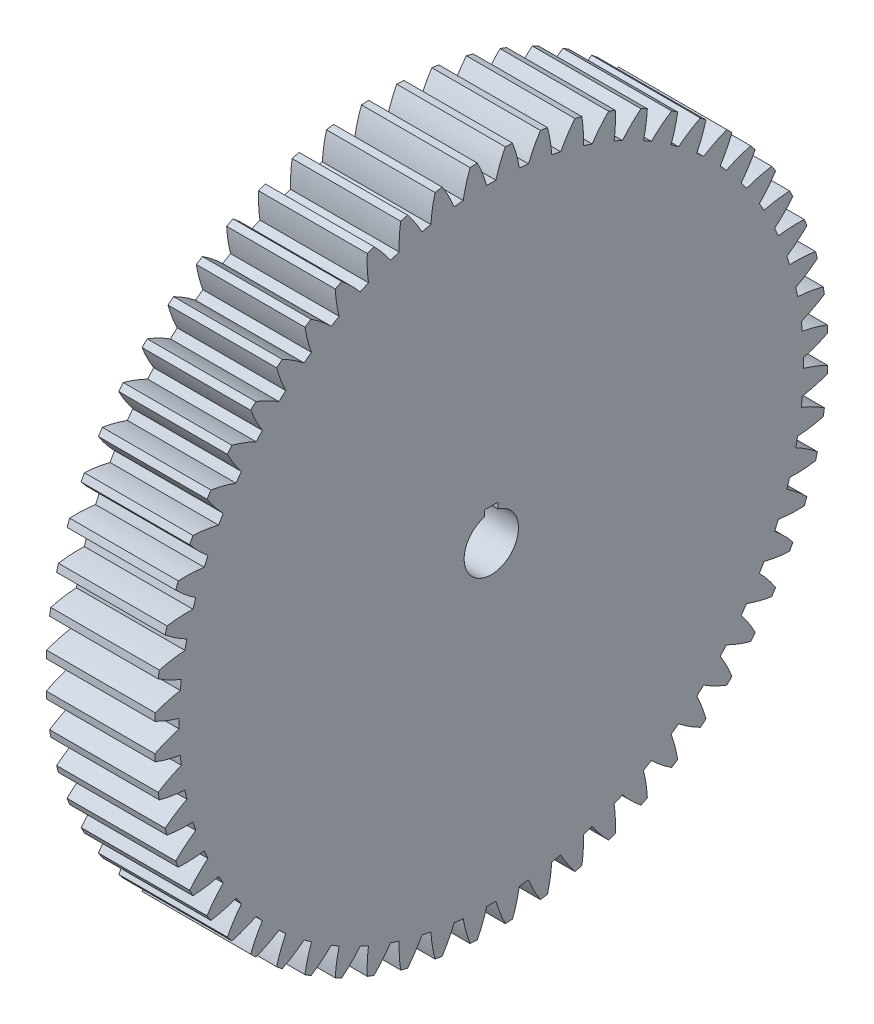
SolidWorks part; units mm, degrees
ref_plane "Plane1" through (0, 0, 0) normal (0, 0, 1) x (1, 0, 0)
ref_plane "Plane2" through (0, 0, 0) normal (0, 1, 0) x (1, 0, 0)
ref_plane "Plane3" through (0, 0, 0) normal (1, 0, 0) x (0, 0, -1)
sketch "HoldingSke" plane through (0, 0, 0) normal (0, 1, 0) x (1, 0, 0)
  line L0 (0, 0) -> (0.1, -0.1732)
  line L1 (-15, 0) -> (100, 0) construction
  line L2 (0, 0) -> (-2.1039, 2.3779)
  line L3 (0, 0) -> (-11.863, 4.5341)
  line L4 (0, 0) -> (4.318, 7.479)
  line L5 (0, 0) -> (-46.8476, -17.4728)
  line L6 (0, 0) -> (-41.4481, -27.9652)
  line L7 (-2.1039, 2.3779) -> (8.6586, 51.2059)
  line L8 (-76.2, 54.61) -> (-72.9, 54.61)
  line L9 (-71.009, 38.7566) -> (-53.1078, 45.2721)
  line L10 (-76.2, 71.12) -> (104.1128, 71.12)
  line L11 (0, 0) -> (-50, 0)
  line L12 (-76.2, 101.6) -> (-76.033, 101.6)
  line L13 (24.9733, 27.94) -> (52.9518, 28.4284)
  line L14 (24.9733, 27.94) -> (24.9743, 27.94)
  line L15 (24.9733, 27.94) -> (100.4006, 29.5858)
  line L16 (-63.627, -5) -> (-12.827, -5)
  circle A0 centre (0, 0) radius 12.5
  circle A1 centre (0, 0) radius 37.5
  circle A2 centre (0, 0) radius 37.5
  circle A3 centre (0, 0) radius 12.5
  dimension "MHD" = 75
  dimension "Hub_dia" = 75
  dimension "Bore" = 25
  dimension "MBD" = 25
  dimension "Num_teeth" = 60
  dimension "Pitch_radius" = 180.3128
  dimension "Pitch" = 0.2
  dimension "Width" = 50
  dimension "Overall_len" = 50
  dimension "Show_teeth" = 60
  dimension "Thickness" = 50
  dimension "OAL" = 50.0001
  dimension "T_dim" = 3.3
  dimension "Ap" = 20
  dimension "H" = 19.05
  dimension "Backlash" = 0.167
  dimension "Addendum_fac" = 1
  dimension "Dedendum_fac" = 1.25
  dimension "Clearance_fac" = 0.25
  dimension "Dedendum_add" = 0.001
  dimension "Module" = 5
sketch "BasProSke" plane through (0, 0, 0) normal (0, 1, 0) x (1, 0, 0)
  line L0 (-10, 0) -> (60, 0) construction
  line L1 (0, 0) -> (0, 155)
  line L2 (0, 0) -> (50, 0)
  line L3 (50, 0) -> (50, 155)
  line L4 (50, 155) -> (0, 155)
  dimension "Diameter" = 310
  dimension "Thickness" = 50
revolve "Base-Revolve" add sketch "BasProSke" angle 360 about L0
sketch "TooCutSke" plane through (0, 0, 0) normal (1, 0, 0) x (0, 0, -1)
  line L1 (0, 0) -> (0, 107) construction
  line L2 (0, 0) -> (-4.2188, 149.9407) construction
  line L3 (0, 0) -> (-15.6962, 299.5009) construction
  line L4 (-4.2188, 149.9407) -> (-7.8481, 149.7505) construction
  arc A0 (2.1133, 143.7335) -> (-2.1133, 143.7335) centre (0, 0) ccw
  arc A1 (6.4708, 154.8903) -> (-6.4708, 154.8903) centre (0, 0) ccw
  circle A2 centre (0, 0) radius 150 construction
  circle A3 centre (0, 0) radius 140.9539 construction
  arc A4 (-2.1133, 143.7335) -> (-6.4708, 154.8903) centre (-59.9014, 127.5924) ccw
  arc A5 (6.4708, 154.8903) -> (2.1133, 143.7335) centre (59.9014, 127.5924) ccw
  dimension "Root_dia" = 287.498
  dimension "Overcut_dia" = 310.0508
  dimension "Pitch_dia" = 300
  dimension "Base_dia" = 281.9078
  dimension "Flank_rad" = 60
  dimension "Half_ang" = 3
  dimension "Half_CT" = 3.6343
extrude "ToothCut" cut sketch "TooCutSke" along normal through all
fillet "Breaks" [suppressed] radius 0.1
fillet "RootFillets" [suppressed] radius 1.251
pattern_circular "TeethCuts" count 60 every 6 about axis through (-10, 0, 0) along (1, 0, 0) of "ToothCut", "RootFillets", "Breaks"
sketch "HubNeaOneSke" plane through (0, 0, 0) normal (-1, 0, 0) x (0, 0, 1)
  circle A0 centre (0, 0) radius 37.5
  dimension "Diameter" = 75
extrude "HubNearOne" [suppressed] add sketch "HubNeaOneSke" along normal blind 12.7001
sketch "HubNeaBotSke" plane through (0, 0, 0) normal (-1, 0, 0) x (0, 0, 1)
  circle A0 centre (0, 0) radius 37.5
  dimension "Diameter" = 75
extrude "HubNearBoth" [suppressed] add sketch "HubNeaBotSke" along normal blind 6.35
ref_plane "FarPln" through (50, 0, 0) normal (1, 0, 0) x (0, 0, -1)
sketch "HubFarSke" plane through (50, 0, 0) normal (1, 0, 0) x (0, 0, -1)
  circle A0 centre (0, 0) radius 37.5
  dimension "Diameter" = 75
extrude "HubFar" [suppressed] add sketch "HubFarSke" along normal blind 6.35
sketch "BorSke" plane through (0, 0, 0) normal (1, 0, 0) x (0, 0, -1)
  circle A0 centre (0, 0) radius 12.5
  dimension "Diameter" = 25
extrude "Bore" cut sketch "BorSke" along normal mid plane 100.0001
sketch "KeySke" plane through (0, 0, 0) normal (1, 0, 0) x (0, 0, -1)
  line L0 (-3.175, 0) -> (-3.175, 14.8812)
  line L1 (-3.175, 14.8812) -> (3.175, 14.8812)
  line L2 (3.175, 14.8812) -> (3.175, 0)
  line L3 (0, 0) -> (0, 34) construction
  line L4 (-3.175, 0) -> (3.175, 0)
  dimension "Offset" = 14.8812
  dimension "Width" = 6.35
extrude "Keyway" cut sketch "KeySke" along normal mid plane 100.0001
pattern_circular "Keyway2" [suppressed] count 2 every 90 about axis through (-10, 0, 0) along (1, 0, 0)
equation "' \"Module@HoldingSke\" = 6.35"
equation "' \"Num_teeth@HoldingSke\" = 12"
equation "' \"Ap@HoldingSke\" =  20"
equation "' \"Width@HoldingSke\" = 0.5 * 25.4"
equation "' \"Hub_dia@HoldingSke\"= 1 * 25.4"
equation "' \"Overall_len@HoldingSke\" = 1.0 * 25.4"
equation "' \"Bore@HoldingSke\" = 0.75 * 25.4"
equation "' \"T_dim@HoldingSke\" = 0.1 * 25.4"
equation "' \"Width@KeySke\" = 0.25 * 25.4"
equation "' \"Show_teeth@HoldingSke\" = 13"
equation "' \"Backlash@HoldingSke\" = 0.009 * 25.4"
equation "' \"Addendum_fac@HoldingSke\" = 1.0"
equation "' \"Dedendum_fac@HoldingSke\" = 1.25"
equation "' \"Dedendum_add@HoldingSke\" = 0.00005 * 25.4"
equation "' \"Clearance_fac@HoldingSke\" = 0.25"
equation "\"Pitch@HoldingSke\" = 1 / \"Module@HoldingSke\""
equation "\"Overcut_dia@TooCutSke\" = (\"Num_teeth@HoldingSke\" + 2 * \"Addendum_fac@HoldingSke\") / \"Pitch@HoldingSke\" + 0.002 * 25.4"
equation "\"Pitch_dia@TooCutSke\" = \"Num_teeth@HoldingSke\" / \"Pitch@HoldingSke\""
equation "\"Base_dia@TooCutSke\" = \"Num_teeth@HoldingSke\" / \"Pitch@HoldingSke\" * cos((\"Ap@HoldingSke\"  * 3.14159265 / 180))"
equation "\"Root_dia@TooCutSke\" = (\"Num_teeth@HoldingSke\" + 2) / \"Pitch@HoldingSke\" - 2 * (\"Addendum_fac@HoldingSke\" + \"Dedendum_fac@HoldingSke\") / \"Pitch@HoldingSke\" - \"Dedendum_add@HoldingSke\" * 2"
equation "\"Half_ang@TooCutSke\" = 180 / \"Num_teeth@HoldingSke\""
equation "\"Half_CT@TooCutSke\" = \"Num_teeth@HoldingSke\" / \"Pitch@HoldingSke\" * sin((3.14159265 / 2 / \"Num_teeth@HoldingSke\")) / 2 - 7 * \"Backlash@HoldingSke\" / 4"
equation "\"Flank_rad@TooCutSke\" = \"Num_teeth@HoldingSke\" / \"Pitch@HoldingSke\" / 5"
equation "\"Radius@RootFillets\" = \"Clearance_fac@HoldingSke\" / \"Pitch@HoldingSke\" + \"Dedendum_add@HoldingSke\""
equation "\"Break_rad@Breaks\" = 0.02 / \"Pitch@HoldingSke\""
equation "\"Thickness@HoldingSke\" = \"Width@HoldingSke\""
equation "\"OAL@HoldingSke\" = \"Thickness@HoldingSke\""
equation "\"MHD@HoldingSke\" = (\"Num_teeth@HoldingSke\" + 2) / \"Pitch@HoldingSke\" - 2 * (\"Addendum_fac@HoldingSke\" + \"Dedendum_fac@HoldingSke\")  / \"Pitch@HoldingSke\" - \"Dedendum_add@HoldingSke\" * 2"
equation "\"MBD@HoldingSke\" = (\"Num_teeth@HoldingSke\" + 2) / \"Pitch@HoldingSke\" - 2 * (\"Addendum_fac@HoldingSke\" + \"Dedendum_fac@HoldingSke\")  / \"Pitch@HoldingSke\" - \"Dedendum_add@HoldingSke\" * 2 - 0.002 * 25.4"
equation "\"MHD@HoldingSke\" = ((sgn( \"MHD@HoldingSke\" - \"Hub_dia@HoldingSke\" )-1)*( \"MHD@HoldingSke\" - \"Hub_dia@HoldingSke\" ))/-2+ \"Hub_dia@HoldingSke\""
equation "\"MBD@HoldingSke\" = ((sgn( \"MBD@HoldingSke\" - \"Bore@HoldingSke\" )-1)*( \"MBD@HoldingSke\" - \"Bore@HoldingSke\" ))/-2+ \"Bore@HoldingSke\""
equation "\"OAL@HoldingSke\" = ((sgn( \"OAL@HoldingSke\" - \"Overall_len@HoldingSke\" )+1)*( \"OAL@HoldingSke\" - \"Overall_len@HoldingSke\" ))/2 + \"Overall_len@HoldingSke\" + 0.000002 * 25.4"
equation "\"Num_teeth@TeethCuts\" = int( \"Show_teeth@HoldingSke\" ) + 1"
equation "\"Num_teeth@TeethCuts\" = ((sgn( \"Num_teeth@TeethCuts\" - \"Num_teeth@HoldingSke\" )-1)*( \"Num_teeth@TeethCuts\" - \"Num_teeth@HoldingSke\" ))/-2+ \"Num_teeth@HoldingSke\""
equation "\"Num_teeth@TeethCuts\" = ((sgn( \"Num_teeth@TeethCuts\" - 2.0)+1)*( \"Num_teeth@TeethCuts\" - 2.0))/2 +2.0"
equation "\"Angle@TeethCuts\" = 360.0 / \"Num_teeth@HoldingSke\""
equation "\"Diameter@BasProSke\" = (\"Num_teeth@HoldingSke\" + 2 * \"Addendum_fac@HoldingSke\") / \"Pitch@HoldingSke\""
equation "\"Thickness@BasProSke\"  = \"Thickness@HoldingSke\""
equation "' \"Fillet_rad@BasProSke\" =  \"Thickness@HoldingSke\" * 0.05"
equation "\"MHD@HoldingSke\" = ((sgn( \"MHD@HoldingSke\" - \"Root_dia@TooCutSke\" )-1)*( \"MHD@HoldingSke\" - \"Root_dia@TooCutSke\" ))/-2+ \"Root_dia@TooCutSke\""
equation "\"Diameter@HubNeaOneSke\" = \"MHD@HoldingSke\""
equation "\"Length@HubNearOne\" = \"OAL@HoldingSke\" - \"Thickness@BasProSke\""
equation "\"Diameter@HubNeaBotSke\" = \"MHD@HoldingSke\""
equation "\"Length@HubNearBoth\" = ( \"OAL@HoldingSke\" - \"Thickness@BasProSke\" ) / 2.0"
equation "\"Thickness@FarPln\" = \"Thickness@BasProSke\""
equation "\"Diameter@HubFarSke\" = \"MHD@HoldingSke\""
equation "\"Length@HubFar\" = ( \"OAL@HoldingSke\" - \"Thickness@BasProSke\" ) / 2.0"
equation "\"Diameter@BorSke\" = \"MBD@HoldingSke\""
equation "\"D1@Bore\" = \"OAL@HoldingSke\" * 2.0"
equation "\"D1@Keyway\" = \"OAL@HoldingSke\" * 2.0"
